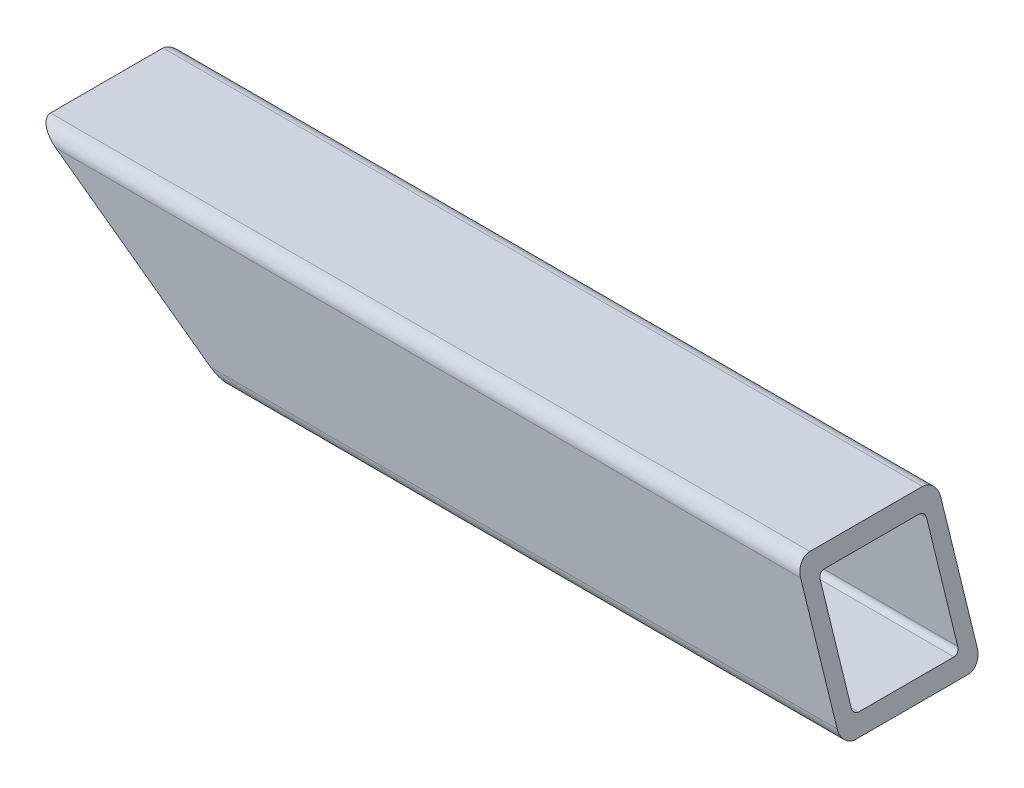
SolidWorks part; units mm, degrees
ref_plane "Front Plane" through (0, 0, 0) normal (0, 0, 1) x (1, 0, 0)
ref_plane "Top Plane" through (0, 0, 0) normal (0, 1, 0) x (1, 0, 0)
ref_plane "Right Plane" through (0, 0, 0) normal (1, 0, 0) x (0, 0, -1)
sketch "Sketch3" plane through (0, 0, 0) normal (1, 0, 0) x (0, 0, -1)
  line L1 (-12.7, 12.7) -> (12.7, 12.7)
  line L2 (-12.7, 12.7) -> (-12.7, -12.7)
  line L3 (-12.7, -12.7) -> (12.7, -12.7)
  line L4 (12.7, 12.7) -> (12.7, -12.7)
  line L5 (-12.7, 12.7) -> (12.7, -12.7) construction
  line L6 (-12.7, -12.7) -> (12.7, 12.7) construction
  line L7 (-9.652, -9.652) -> (9.652, -9.652)
  line L8 (-9.652, -9.652) -> (-9.652, 9.652)
  line L9 (-9.652, 9.652) -> (9.652, 9.652)
  line L10 (9.652, -9.652) -> (9.652, 9.652)
  line L11 (-9.652, -9.652) -> (9.652, 9.652) construction
  line L12 (-9.652, 9.652) -> (9.652, -9.652) construction
  point P0 (0, 0)
  point P6 (0, 0)
  dimension "D1" = 25.4
  dimension "D2" = 19.304
  dimension "D3" = 19.304
  dimension "D4" = 25.4
extrude "Boss-Extrude1" add sketch "Sketch3" against normal blind 145.89
fillet "Fillet1" radius 2.5 4 edges at (-72.945, -12.7, -12.7) (-72.945, -12.7, 12.7) (-72.945, 12.7, -12.7) (-72.945, 12.7, 12.7)
fillet "Fillet2" radius 1 4 edges at (-72.945, -9.652, -9.652) (-72.945, 9.652, -9.652) (-72.945, 9.652, 9.652) (-72.945, -9.652, 9.652)
sketch "Sketch5" plane through (0, 0, -12.7) normal (0, 0, -1) x (-1, 0, 0)
  line L0 (145.89, 12.7) -> (110.9299, -12.7)
  line L1 (0, -12.7) -> (145.89, -12.7) construction
  line L2 (110.9299, -12.7) -> (145.89, -12.7)
  line L3 (145.89, -12.7) -> (145.89, 12.7)
  line L4 (0, 12.7) -> (8.253, 12.7)
  line L5 (145.89, 12.7) -> (0, 12.7) construction
  line L6 (8.253, 12.7) -> (0, -12.7)
  line L7 (0, -12.7) -> (0, 12.7)
  dimension "D1" = 36
  dimension "D2" = 18
extrude "Cut-Extrude1" cut sketch "Sketch5" against normal through all
